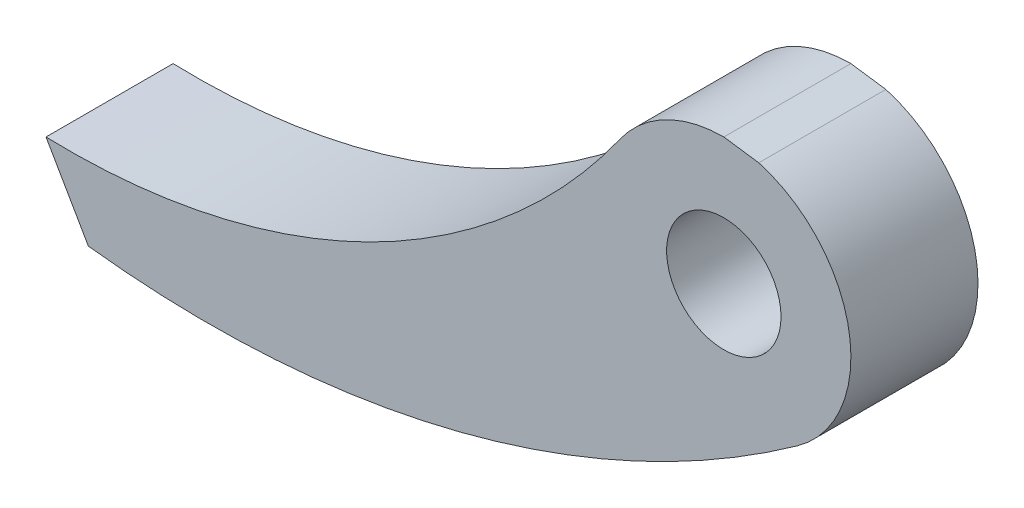
SolidWorks part; units mm, degrees
ref_plane "Front Plane" through (0, 0, 0) normal (0, 0, 1) x (1, 0, 0)
ref_plane "Top Plane" through (0, 0, 0) normal (0, 1, 0) x (1, 0, 0)
ref_plane "Right Plane" through (0, 0, 0) normal (1, 0, 0) x (0, 0, -1)
sketch "Sketch1" plane through (0, 0, 0) normal (0, 0, 1) x (1, 0, 0)
  line L0 (0, 3) -> (0.8245, 2.8845)
  line L1 (0, -3) -> (0.8245, -2.8845)
  line L2 (0, 0) -> (-20, 0) construction
  line L3 (-16, -5) -> (-15, -6.7321)
  circle A0 centre (0, 0) radius 1.35
  circle A1 centre (0, 0) radius 3
  arc A3 (-16, -5) -> (-2.447, 1.7356) centre (-15.4975, 10.9921) ccw
  arc A4 (-15, -6.7321) -> (1.7409, -2.4432) centre (-12.1863, 17.1024) ccw
  point P15 (-2.0187, 9.0534)
  point P16 (-20, 0)
  point P17 (0, 0)
  point P18 (0, 0)
  point P19 (0, 0)
  dimension "D1" = 2.7
  dimension "D2" = 6
  dimension "D6" = 16
  dimension "D7" = 24
  dimension "D3" = 60
  dimension "D4" = 15
  dimension "D5" = 2
  dimension "D8" = 5
extrude "Pawl" add sketch "Sketch1" along normal mid plane 3
